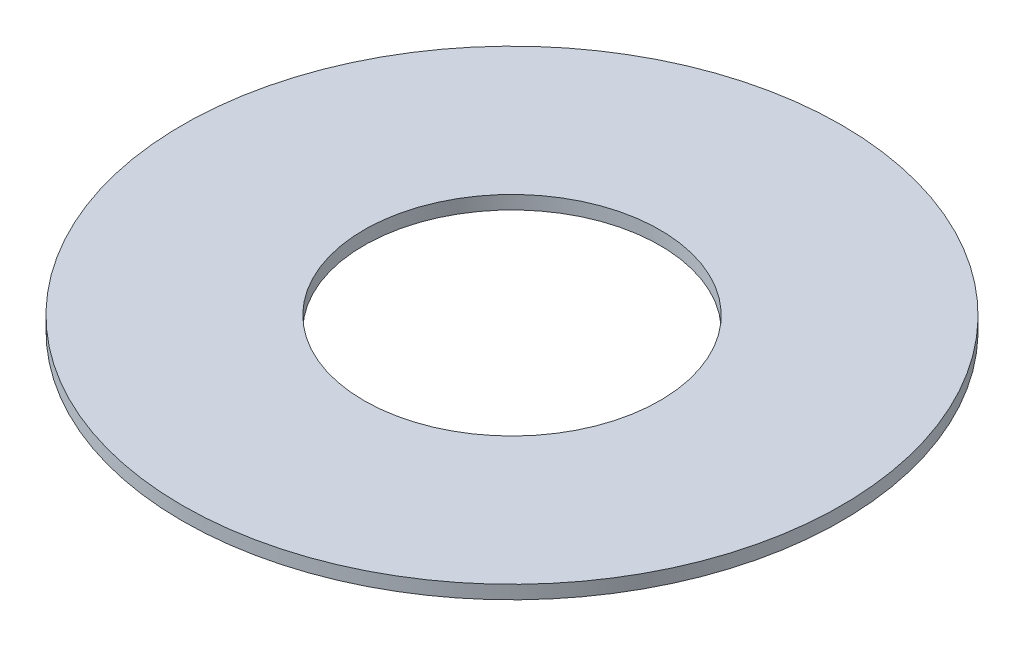
SolidWorks part; units mm, degrees
material "PTFE (general)"
ref_plane "Front Plane" through (0, 0, 0) normal (0, 0, 1) x (1, 0, 0)
ref_plane "Top Plane" through (0, 0, 0) normal (0, 1, 0) x (1, 0, 0)
ref_plane "Right Plane" through (0, 0, 0) normal (1, 0, 0) x (0, 0, -1)
sketch "Sketch1" plane through (0, 0, 0) normal (0, 1, 0) x (1, 0, 0)
  circle A0 centre (0, 0) radius 49
  circle A1 centre (0, 0) radius 22
  dimension "D1" = 44
  dimension "D2" = 98
extrude "Boss-Extrude1" add sketch "Sketch1" along normal blind 2
